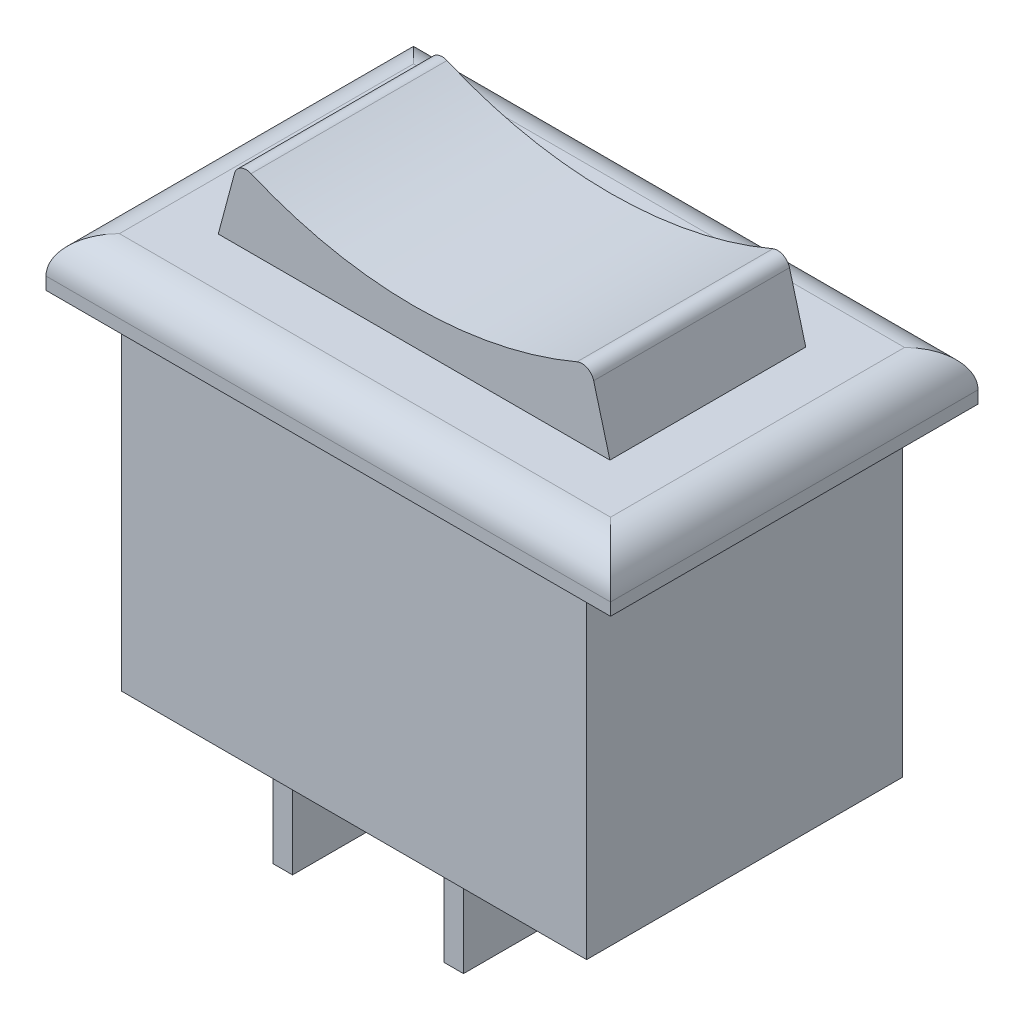
SolidWorks part; units mm, degrees
ref_plane "Front Plane" through (0, 0, 0) normal (0, 0, 1) x (1, 0, 0)
ref_plane "Top Plane" through (0, 0, 0) normal (0, 1, 0) x (1, 0, 0)
ref_plane "Right Plane" through (0, 0, 0) normal (1, 0, 0) x (0, 0, -1)
sketch "Sketch1" plane through (0, 0, 0) normal (0, 0, 1) x (1, 0, 0)
  line L0 (-2.032, 0) -> (0, 0)
  line L1 (0, 0) -> (18.9992, 0) construction
  line L2 (0, 0) -> (0, -13.6906)
  line L3 (0, -13.6906) -> (18.9992, -13.6906)
  line L4 (18.9992, 0) -> (18.9992, -13.6906)
  line L5 (21.0312, 2.0066) -> (-2.032, 2.0066)
  line L6 (21.0312, 2.0066) -> (21.0312, 0)
  line L7 (21.0312, 0) -> (-2.032, 0) construction
  line L8 (-2.032, 2.0066) -> (-2.032, 0)
  line L9 (21.0312, 0) -> (18.9992, 0)
  point P9 (9.4996, 0)
  point P10 (9.4996, 0)
  dimension "D1" = 18.9992
  dimension "D2" = 13.6906
  dimension "D3" = 2.0066
  dimension "D4" = 2.032
extrude "Boss-Extrude1" add sketch "Sketch1" along normal blind 15.0114
sketch "Sketch2" plane through (21.0312, 0, 0) normal (1, 0, 0) x (0, 0, -1)
  line L0 (-15.0114, 0) -> (0, 0) construction
  line L1 (-15.0114, -13.6906) -> (-13.9573, -13.6906)
  line L2 (-15.0114, -13.6906) -> (-15.0114, 0)
  line L3 (-15.0114, 0) -> (-13.9573, 0)
  line L4 (-13.9573, -13.6906) -> (-13.9573, 0)
  line L6 (0, -13.6906) -> (-1.0541, -13.6906)
  line L7 (0, -13.6906) -> (0, 0)
  line L8 (0, 0) -> (-1.0541, 0)
  line L9 (-1.0541, -13.6906) -> (-1.0541, 0)
  dimension "D1" = 12.9032
extrude "Cut-Extrude1" cut sketch "Sketch2" against normal through all
fillet "Fillet1" radius 1.5 4 edges at (21.0312, 2.0066, 7.5057) (9.4996, 2.0066, 15.0114) (-2.032, 2.0066, 7.5057) (9.4996, 2.0066, 0)
sketch "Sketch4" plane through (0, 0, 13.9573) normal (0, 0, 1) x (1, 0, 0)
  line L0 (0, -13.6906) -> (18.9992, -13.6906) construction
  line L1 (2.1209, -13.6906) -> (2.9083, -13.6906)
  line L2 (2.1209, -13.6906) -> (2.1209, -20.7772)
  line L3 (2.1209, -20.7772) -> (2.9083, -20.7772)
  line L4 (2.9083, -13.6906) -> (2.9083, -20.7772)
  line L5 (9.4996, 0) -> (9.4996, -23.1558) construction
  line L6 (9.1059, -13.6906) -> (9.8933, -13.6906)
  line L7 (9.1059, -13.6906) -> (9.1059, -20.7772)
  line L8 (9.1059, -20.7772) -> (9.8933, -20.7772)
  line L9 (9.8933, -13.6906) -> (9.8933, -20.7772)
  line L10 (0, 0) -> (18.9992, 0) construction
  point P14 (9.4996, -20.7772)
  point P15 (2.5146, -20.7772)
  dimension "D1" = 7.0866
  dimension "D2" = 0.7874
  dimension "D3" = 6.985
extrude "Boss-Extrude2" add sketch "Sketch4" against normal up to surface (12.9032 mm away) up to face at (9.4996, -6.8453, 1.0541)
sketch "Sketch5" plane through (0, 0, 0) normal (-1, 0, 0) x (0, 0, 1)
  line L0 (1.0541, -20.7772) -> (13.9573, -20.7772) construction
  line L1 (1.0541, -13.6906) -> (5.1308, -13.6906)
  line L2 (1.0541, -13.6906) -> (1.0541, -20.7772)
  line L3 (1.0541, -20.7772) -> (5.1308, -20.7772)
  line L4 (5.1308, -13.6906) -> (5.1308, -20.7772)
  line L6 (13.9573, -13.6906) -> (9.8806, -13.6906)
  line L7 (13.9573, -13.6906) -> (13.9573, -20.7772)
  line L8 (13.9573, -20.7772) -> (9.8806, -20.7772)
  line L9 (9.8806, -13.6906) -> (9.8806, -20.7772)
  dimension "D1" = 4.7498
extrude "Cut-Extrude2" cut sketch "Sketch5" against normal through all
ref_plane "Plane1" through (0, 0, 7.5057) normal (0, 0, 1) x (1, 0, 0)
sketch "Sketch6" plane through (0, 0, 7.5057) normal (0, 0, 1) x (1, 0, 0)
  line L0 (2.1633, 4.4836) -> (1.4996, 2.0066)
  line L1 (-0.532, 2.0066) -> (19.5312, 2.0066) construction
  line L2 (16.8359, 4.4836) -> (17.4996, 2.0066)
  line L3 (1.4996, 2.0066) -> (17.4996, 2.0066)
  line L4 (0, 0) -> (18.9992, 0) construction
  arc A0 (2.8421, 4.8142) -> (16.1571, 4.8142) centre (9.4996, 20.4564) ccw
  arc A1 (16.1571, 4.8142) -> (16.8359, 4.4836) centre (16.3529, 4.3542) cw
  arc A2 (2.8421, 4.8142) -> (2.1633, 4.4836) centre (2.6463, 4.3542) ccw
  point P9 (9.4996, 0)
  point P10 (9.4996, 2.0066)
  point P11 (16.6832, 5.0534)
  point P14 (16.6843, 5.0493)
  dimension "D3" = 17
  dimension "D6" = 0.5
  dimension "D1" = 75
  dimension "D2" = 75
  dimension "D4" = 16
  dimension "D5" = 3.15
extrude "Boss-Extrude3" add sketch "Sketch6" along normal blind 4 and the other way blind 4
